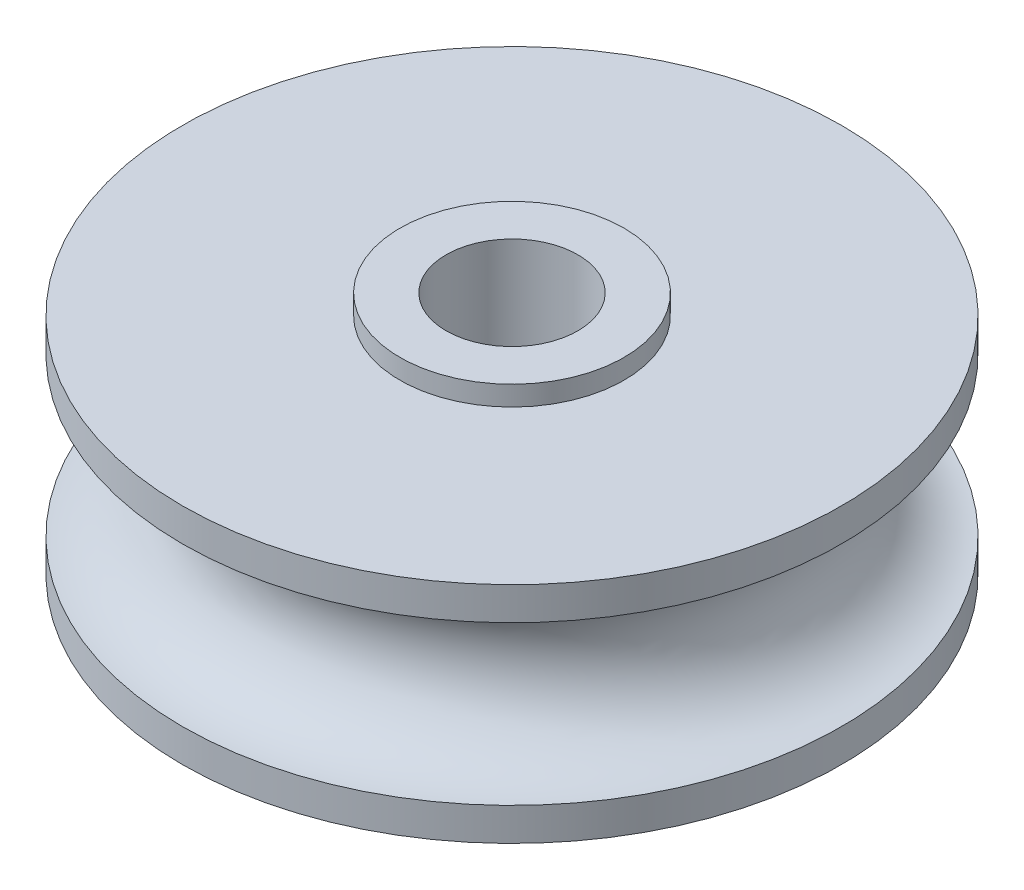
SolidWorks part; units mm, degrees
ref_plane "Front Plane" through (0, 0, 0) normal (0, 0, 1) x (1, 0, 0)
ref_plane "Top Plane" through (0, 0, 0) normal (0, 1, 0) x (1, 0, 0)
ref_plane "Right Plane" through (0, 0, 0) normal (1, 0, 0) x (0, 0, -1)
sketch "Sketch1" plane through (0, 0, 0) normal (0, 0, 1) x (1, 0, 0)
  line L0 (0, 0) -> (0, 10.16)
  line L1 (0, 10.16) -> (4.318, 10.16)
  line L2 (4.318, 10.16) -> (4.318, 9.398)
  line L3 (4.318, 9.398) -> (12.7, 9.398)
  line L4 (12.7, 9.398) -> (12.7, 8.128)
  line L5 (12.7, 2.032) -> (12.7, 0.762)
  line L6 (12.7, 0.762) -> (4.318, 0.762)
  line L7 (4.318, 0.762) -> (4.318, 0)
  line L8 (4.318, 0) -> (0, 0)
  arc A0 (12.7, 8.128) -> (12.7, 2.032) centre (12.7, 5.08) ccw
  point P18 (12.7, 8.763)
  dimension "D1" = 3.048
  dimension "D2" = 10.16
  dimension "D3" = 0.762
  dimension "D4" = 12.7
  dimension "D5" = 4.318
revolve "Revolve1" add sketch "Sketch1" angle 360 about L0
sketch "Sketch2" plane through (0, 10.16, 0) normal (0, 1, 0) x (1, 0, 0)
  circle A0 centre (0, 0) radius 2.54
  dimension "D1" = 5.08
extrude "Cut-Extrude1" cut sketch "Sketch2" against normal through all
